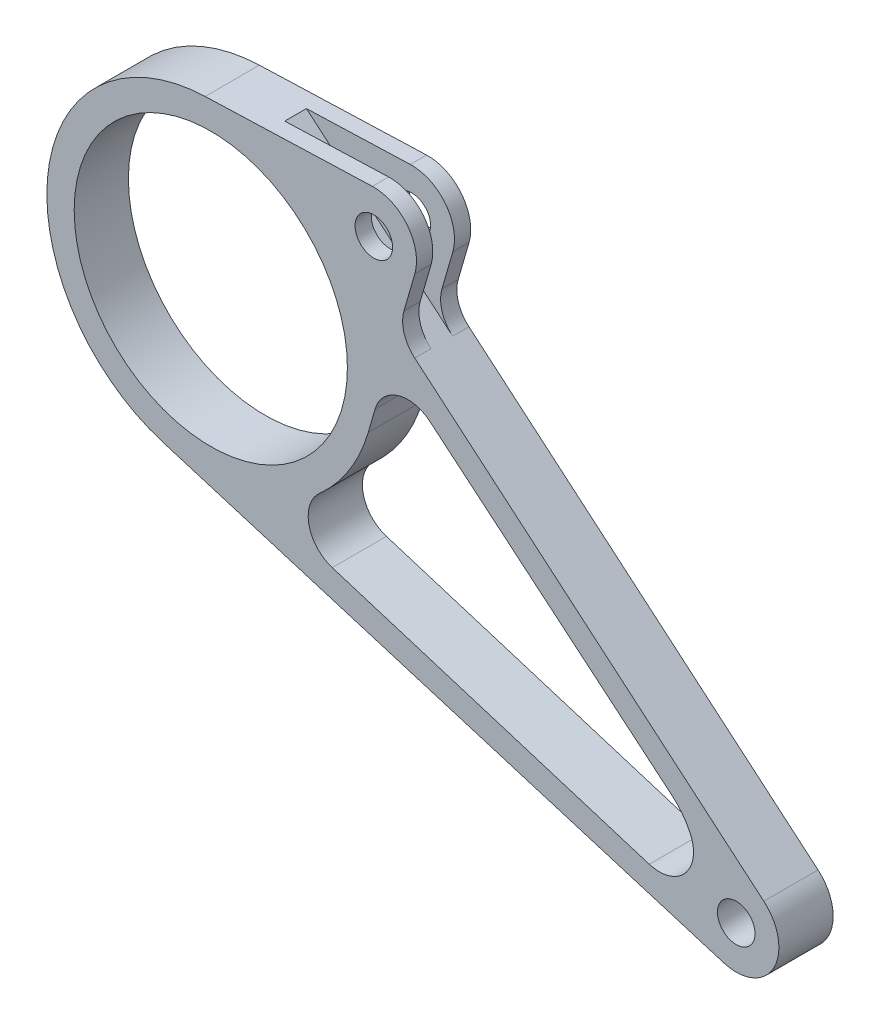
SolidWorks part; units mm, degrees
material "6061-T6 (SS)"
ref_plane "Front Plane" through (0, 0, 0) normal (0, 0, 1) x (1, 0, 0)
ref_plane "Top Plane" through (0, 0, 0) normal (0, 1, 0) x (1, 0, 0)
ref_plane "Right Plane" through (0, 0, 0) normal (1, 0, 0) x (0, 0, -1)
sketch "Sketch2" plane through (0, 0, 0) normal (0, 0, 1) x (1, 0, 0)
  line L0 (0, 0) -> (47.1306, -195.9686) construction
  line L1 (47.1306, -195.9686) -> (-302.8687, -196.6579) construction
  line L2 (-302.8687, -196.6579) -> (-257.3584, -0.3067) construction
  line L3 (-257.3584, -0.3067) -> (0, 0) construction
  line L4 (12.1535, 2.9229) -> (59.2841, -193.0457) construction
  line L5 (-12.1535, -2.9229) -> (34.9771, -198.8916) construction
  line L6 (0.0149, -12.5) -> (-257.3435, -12.8067) construction
  line L7 (-257.3733, 12.1933) -> (-0.0149, 12.5) construction
  line L8 (-269.5356, 2.5158) -> (-315.0459, -193.8355) construction
  line L9 (-290.6915, -199.4803) -> (-245.1812, -3.1291) construction
  line L10 (-302.8441, -209.1579) -> (47.1552, -208.4686) construction
  line L11 (-302.8933, -184.1579) -> (47.106, -183.4687) construction
  line L14 (-0.0149, 12.5) -> (-257.5094, 12.1932) construction
  line L15 (-287.5987, -186.1366) -> (-245.1812, -3.1291) construction
  circle A0 centre (0, 0) radius 12.5 construction
  circle A1 centre (47.1306, -195.9686) radius 12.5 construction
  circle A2 centre (-302.8687, -196.6579) radius 12.5 construction
  circle A3 centre (-257.3584, -0.3067) radius 12.5 construction
  circle A4 centre (47.1306, -195.9686) radius 12.5 construction
  arc A5 (-302.8933, -184.1579) -> (-302.8441, -209.1579) centre (-302.8687, -196.6579) ccw construction
sketch "Sketch4" plane through (0, 0, 0) normal (0, 0, 1) x (1, 0, 0)
  line L0 (-149.2073, -56.7645) -> (-5.3459, 11.2992) construction
  line L1 (-143.8125, -145.7054) -> (43.1897, -207.8311) construction
  line L2 (-128.6792, -100.1534) -> (47.1306, -195.9686) construction
  line L3 (12.1535, 2.9229) -> (59.2841, -193.0457) construction
  line L4 (-128.6792, -100.1534) -> (0, 0) construction
  line L5 (-142.6339, -146.0802) -> (21.5449, -195.9652)
  line L6 (37.2581, -180.7887) -> (-7.6495, -12.1388)
  line L7 (-24.6116, -3.8484) -> (-147.4299, -55.9673)
  line L8 (-257.3584, -0.3067) -> (0, 0) construction
  arc A0 (-149.2073, -56.7645) -> (-143.8125, -145.7054) centre (-128.6792, -100.1534) ccw construction
  arc A1 (-5.3459, 11.2992) -> (12.1535, 2.9229) centre (0, 0) cw construction
  arc A2 (43.1897, -207.8311) -> (59.2841, -193.0457) centre (47.1306, -195.9686) ccw construction
  circle A3 centre (47.1306, -195.9686) radius 12.5 construction
  circle A4 centre (0, 0) radius 12.5 construction
  circle A5 centre (-128.6792, -100.1534) radius 40 construction
  circle A6 centre (-128.6792, -100.1534) radius 121 construction
  circle A7 centre (-128.6792, -100.1534) radius 40
  arc A8 (-147.4299, -55.9673) -> (-142.6339, -146.0802) centre (-128.6792, -100.1534) ccw
  arc A9 (21.5449, -195.9652) -> (37.2581, -180.7887) centre (25.179, -184.0051) ccw
  arc A10 (-7.6495, -12.1388) -> (-24.6116, -3.8484) centre (-19.7286, -15.3552) ccw
  circle A11 centre (25.179, -184.0051) radius 5.5
  circle A12 centre (-19.7286, -15.3552) radius 5.5
  point P29 (-128.6792, -0.1533)
  dimension "D1" = 80
  dimension "D2" = 8
  dimension "D3" = 242
  dimension "D4" = 11
  dimension "D5" = 7
  dimension "D6" = 100
extrude "Boss-Extrude1" add sketch "Sketch4" along normal blind 15.875
sketch "Sketch5" plane through (0, 0, 15.875) normal (0, 0, 1) x (1, 0, 0)
  line L0 (-130.3256, -52.1816) -> (-81.3647, -50.5013)
  line L1 (-82.5798, -113.5266) -> (-68.9308, -66.4765)
  line L2 (23.5494, -189.2582) -> (-140.5308, -138.3573)
  line L3 (-97.6467, -63.534) -> (33.2603, -174.4688)
  line L4 (28.7103, -179.7885) -> (-102.997, -69.4871)
  line L8 (-128.6792, -100.1534) -> (-19.7286, -15.3552) construction
  circle A0 centre (-128.6792, -100.1534) radius 48
  arc A1 (-147.4299, -55.9673) -> (-142.6339, -146.0802) centre (-128.6792, -100.1534) ccw construction
  circle A2 centre (-19.7286, -15.3552) radius 12.5
  circle A3 centre (25.179, -184.0051) radius 12.5
  arc A4 (-7.6495, -12.1388) -> (-24.6116, -3.8484) centre (-19.7286, -15.3552) ccw construction
  circle A5 centre (25.179, -184.0051) radius 5.5 construction
  arc A6 (21.5449, -195.9652) -> (37.2581, -180.7887) centre (25.179, -184.0051) ccw construction
  circle A7 centre (-80.9359, -62.9939) radius 12.5 construction
  arc A8 (-81.3647, -50.5013) -> (-68.9308, -66.4765) centre (-80.9359, -62.9939) cw
  circle A9 centre (-80.9359, -62.9939) radius 5.5
  circle A10 centre (-19.7286, -15.3552) radius 5.5 construction
  circle A11 centre (-128.6792, -100.1534) radius 40 construction
  circle A13 centre (-128.6792, -100.1534) radius 40 construction
extrude "Cut-Extrude2" cut sketch "Sketch5" against normal through all
fillet "Fillet1" radius 10 3 edges at (-76.292, -91.8518, 7.9375) (-115.1892, -146.2188, 7.9375) (-73.912, -83.6475, 7.9375)
fillet "Fillet2" radius 20 1 edges at (20.1046, -172.5815, 7.9375)
fillet "Fillet3" radius 10 1 edges at (12.8284, -185.9323, 7.9375)
sketch "Sketch8" plane through (0, 0, 0) normal (0, 0, 1) x (1, 0, 0)
  line L0 (-257.3584, -0.3067) -> (-346.2284, -83.1582) construction
  line L1 (-346.2284, -83.1582) -> (-302.8687, -196.6579) construction
  circle A0 centre (-346.2284, -83.1582) radius 104 construction
  circle A1 centre (-257.3584, -0.3067) radius 12.5 construction
  circle A2 centre (-302.8687, -196.6579) radius 12.5 construction
  point P2 (-270.1586, -12.24)
  point P3 (-266.5014, -8.8305)
  point P5 (-309.1139, -180.3102)
  point P10 (-307.3296, -184.981)
  dimension "D1" = 208
  dimension "D2" = 5
  dimension "D3" = 5
ref_plane "Plane1" through (0, 0, 7.9375) normal (0, 0, 1) x (1, 0, 0)
sketch "Sketch9" plane through (0, 0, 7.9375) normal (0, 0, 1) x (1, 0, 0)
  line L0 (-87.8247, -54.1431) -> (-83.2277, -50.5652) construction
  line L1 (-74.0472, -71.8447) -> (-81.2366, -77.4404) construction
  line L2 (-128.6792, -100.1534) -> (0, 0) construction
  line L3 (-130.3256, -52.1816) -> (-81.3647, -50.5013) construction
  line L4 (-68.9673, -87.8378) -> (33.2603, -174.4688) construction
  line L5 (-61.2496, -94.3781) -> (-111.7934, -51.5456)
  line L6 (-68.9673, -87.8378) -> (33.2603, -174.4688) construction
  line L7 (-111.7934, -51.5456) -> (-96.4609, -33.4528)
  line L8 (-96.4609, -33.4528) -> (-45.9171, -76.2852)
  line L9 (-45.9171, -76.2852) -> (-61.2496, -94.3781)
  circle A0 centre (-80.9359, -62.9939) radius 11.2157 construction
  circle A2 centre (-80.9359, -44.1073) radius 6.35 construction
  arc A3 (-68.9308, -66.4765) -> (-81.3647, -50.5013) centre (-80.9359, -62.9939) ccw construction
  dimension "D1" = 12.7
extrude "Cut-Extrude3" cut sketch "Sketch9" against normal mid plane 6.35
ref_plane "Plane2" through (-65.6855, -77.5112, 0) normal (0.6465, 0.7629, 0) x (0, 0, -1)
sketch "Sketch10" plane through (0, 0, 7.9375) normal (0, 0, 1) x (1, 0, 0)
  line L0 (-74.0472, -71.8447) -> (-59.3794, -60.4285)
  line L1 (-87.8247, -54.1431) -> (-73.1569, -42.7269)
  line L2 (-73.1569, -42.7269) -> (-59.3794, -60.4285)
  line L3 (-68.9673, -87.8378) -> (33.2603, -174.4688) construction
  line L4 (-128.6792, -100.1534) -> (0, 0) construction
  arc A0 (-87.8247, -54.1431) -> (-74.0472, -71.8447) centre (-80.9359, -62.9939) ccw
  circle A1 centre (-80.9359, -62.9939) radius 5.5
  point P9 (-66.2681, -51.5777)
extrude "Boss-Extrude2" [suppressed] add sketch "Sketch10" along normal mid plane 6.35 separate body
